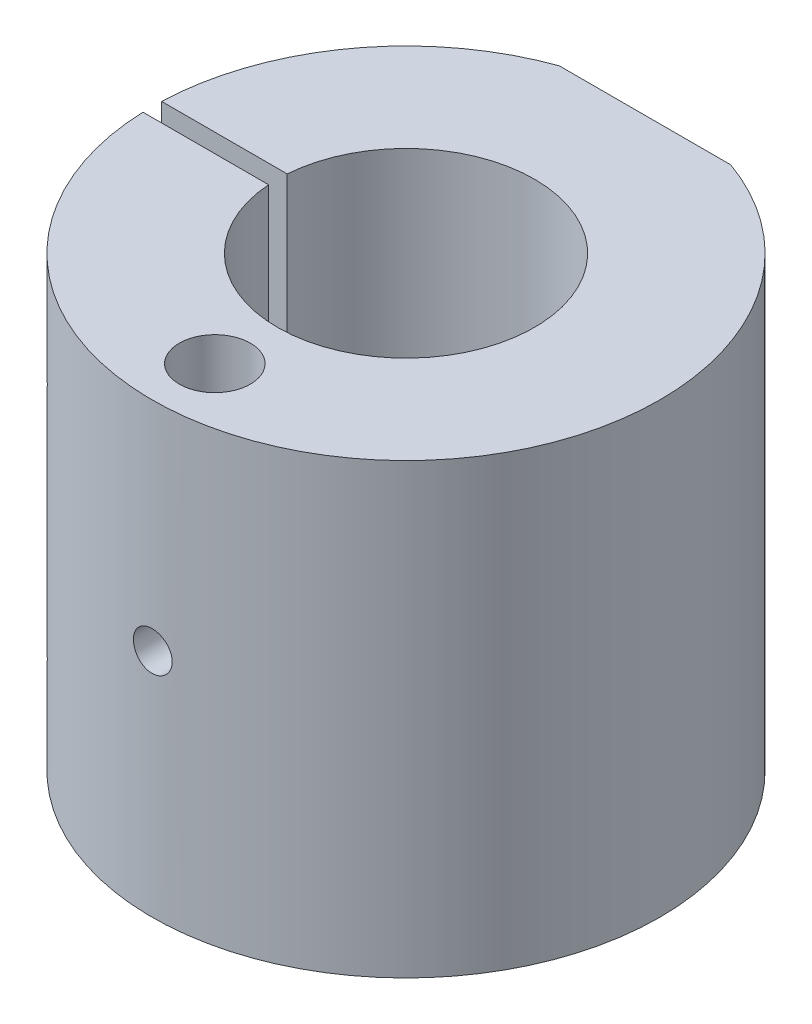
SolidWorks part; units mm, degrees
ref_plane "Front Plane" through (0, 0, 0) normal (0, 0, 1) x (1, 0, 0)
ref_plane "Top Plane" through (0, 0, 0) normal (0, 1, 0) x (1, 0, 0)
ref_plane "Right Plane" through (0, 0, 0) normal (1, 0, 0) x (0, 0, -1)
sketch "Sketch2" plane through (0, 0, 0) normal (0, 1, 0) x (1, 0, 0)
  circle A0 centre (0, 0) radius 10.922
  circle A1 centre (0, 0) radius 21.59
  dimension "D1" = 43.18
  dimension "D2" = 21.844
extrude "Boss-Extrude1" add sketch "Sketch2" along normal blind 38.1
sketch "Sketch3" plane through (0, 38.1, 0) normal (0, 1, 0) x (1, 0, 0)
  line L0 (0, 0) -> (-21.59, 0) construction
  line L1 (0, 0.7937) -> (-21.59, 0.7937)
  line L2 (0, -0.7937) -> (-21.59, -0.7938)
  line L3 (-21.59, 0.7937) -> (-21.59, -0.7938)
  line L4 (0, 0.7937) -> (0, -0.7937)
  circle A0 centre (0, 0) radius 21.59 construction
  dimension "D1" = 0.7937
  dimension "D2" = 0.7937
extrude "Cut-Extrude1" cut sketch "Sketch3" against normal up to next
sketch "Sketch4" plane through (0, 38.1, 0) normal (0, 1, 0) x (1, 0, 0)
  line L0 (0, -10.922) -> (0, -21.59) construction
  arc A0 (-10.8931, -0.7938) -> (-10.8931, 0.7937) centre (0, 0) ccw construction
  arc A1 (-21.5754, -0.7938) -> (-21.5754, 0.7937) centre (0, 0) ccw construction
  circle A2 centre (0, -16.256) radius 3.0226
  dimension "D1" = 6.0452
extrude "Cut-Extrude2" cut sketch "Sketch4" against normal up to next
sketch "Sketch5" plane through (0, 38.1, 0) normal (0, 1, 0) x (1, 0, 0)
  line L0 (7.2956, 20.32) -> (-7.2956, 20.32)
  arc A0 (-21.5754, -0.7938) -> (-21.5754, 0.7937) centre (0, 0) ccw construction
  arc A1 (7.2956, 20.32) -> (-7.2956, 20.32) centre (0, 0) ccw
  dimension "D1" = 20.32
extrude "Cut-Extrude3" cut sketch "Sketch5" against normal up to next
sketch "Sketch6" plane through (0, 0, -20.32) normal (0, 0, -1) x (-1, 0, 0)
  line L0 (0, 38.1) -> (0, 0) construction
  line L1 (7.2956, 38.1) -> (-7.2956, 38.1) construction
  line L2 (-7.2956, 0) -> (7.2956, 0) construction
  circle A0 centre (0, 19.05) radius 0.5591 construction
hole_wizard "Tap Drill for M3x0.5 Tap1" positions "3DSketch1" profile "Sketch7" hole size "M3x0.5" standard "ANSI Metric"
sketch3d "3DSketch1"
  point P0 (0, 19.05, -20.32)
sketch "Sketch7" plane through (0, 19.05, -20.32) normal (1, 0, 0) x (0, 1, 0)
  line L0 (0, 0) -> (0, 5.3231)
  line L1 (0, 5.3231) -> (1.25, 4.572)
  line L2 (1.25, 4.572) -> (1.25, 0)
  line L5 (1.25, 0) -> (0, 0)
  line L10 (0, 5.3231) -> (-1.25, 4.572) construction
  line L11 (0, -6.35) -> (0, 107.95) construction
  dimension "Hole Dia." = 2.5
  dimension "Hole Depth" = 4.572
  dimension "Drill Angle" = 118
ref_plane "Plane1" through (0, 0, 21.59) normal (0, 0, 1) x (1, 0, 0)
sketch "Sketch8" plane through (0, 0, 21.59) normal (0, 0, 1) x (1, 0, 0)
  line L0 (0.0073, 38.1) -> (0.0073, 0) construction
  line L1 (21.59, 38.1) -> (-21.5754, 38.1) construction
  line L2 (-21.5754, 0) -> (21.59, 0) construction
  circle A0 centre (0, 19.6091) radius 1.65
  circle A1 centre (0, 19.05) radius 0.5591 construction
  dimension "D1" = 3.3
extrude "Cut-Extrude4" cut sketch "Sketch8" against normal up to next
sketch "Sketch9" plane through (0, 0, 0.7937) normal (0, 0, -1) x (-1, 0, 0)
  line L0 (16.2343, 0) -> (16.2343, 38.1) construction
  line L1 (10.8931, 0) -> (21.5754, 0) construction
  line L2 (21.5754, 38.1) -> (10.8931, 38.1) construction
  circle A0 centre (16.2343, 29.1092) radius 1.0697 construction
  circle A1 centre (16.2343, 8.904) radius 1.0697 construction
hole_wizard "Tap Drill for M4x0.7 Tap1" positions "3DSketch4" profile "Sketch10" hole size "M4x0.7" standard "ANSI Metric"
sketch3d "3DSketch4"
  point P0 (-16.2343, 29.1092, 0.7938)
  point P3 (-16.2343, 8.904, 0.7938)
sketch "Sketch10" plane through (-16.2343, 29.1092, 0.7938) normal (1, 0, 0) x (0, 1, 0)
  line L0 (0, 0) -> (0, 13.4392)
  line L1 (0, 13.4392) -> (1.65, 13.4392)
  line L2 (1.65, 13.4392) -> (1.65, 0)
  line L5 (1.65, 0) -> (0, 0)
  line L11 (0, -6.35) -> (0, 107.95) construction
  dimension "Thru Hole Dia." = 3.3
  dimension "Thru Hole Depth" = 13.4392
